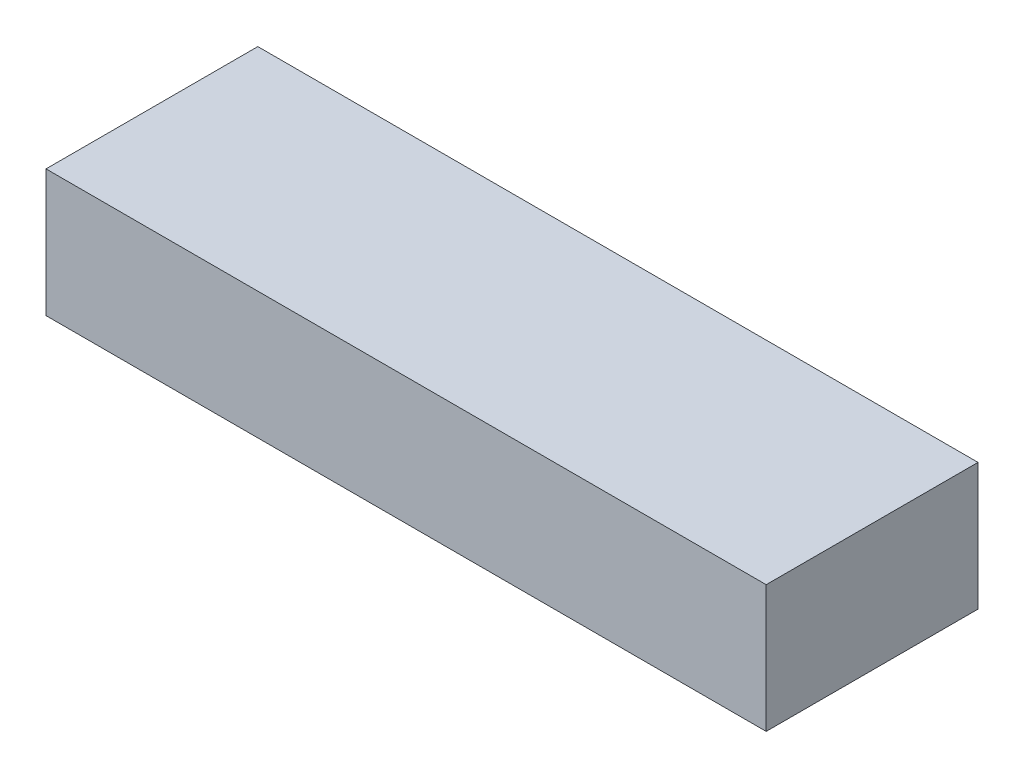
SolidWorks part; units mm, degrees
ref_plane "Front Plane" through (0, 0, 0) normal (0, 0, 1) x (1, 0, 0)
ref_plane "Top Plane" through (0, 0, 0) normal (0, 1, 0) x (1, 0, 0)
ref_plane "Right Plane" through (0, 0, 0) normal (1, 0, 0) x (0, 0, -1)
other "Bounding Box"
ref_plane "Default Plane" through (-8.9266, -12.7485, 0) normal (-0.1736, 0.9848, 0) x (0.9848, 0.1736, 0)
sketch "Sketch1" plane through (0, 0, 0) normal (0, 1, 0) x (1, 0, 0)
  line L1 (-34, 10) -> (34, 10)
  line L2 (-34, 10) -> (-34, -10)
  line L3 (-34, -10) -> (34, -10)
  line L4 (34, 10) -> (34, -10)
  line L5 (-34, 10) -> (34, -10) construction
  line L6 (-34, -10) -> (34, 10) construction
  point P0 (0, 0)
  dimension "D1" = 68
  dimension "D2" = 20
extrude "Boss-Extrude1" add sketch "Sketch1" along normal mid plane 12
